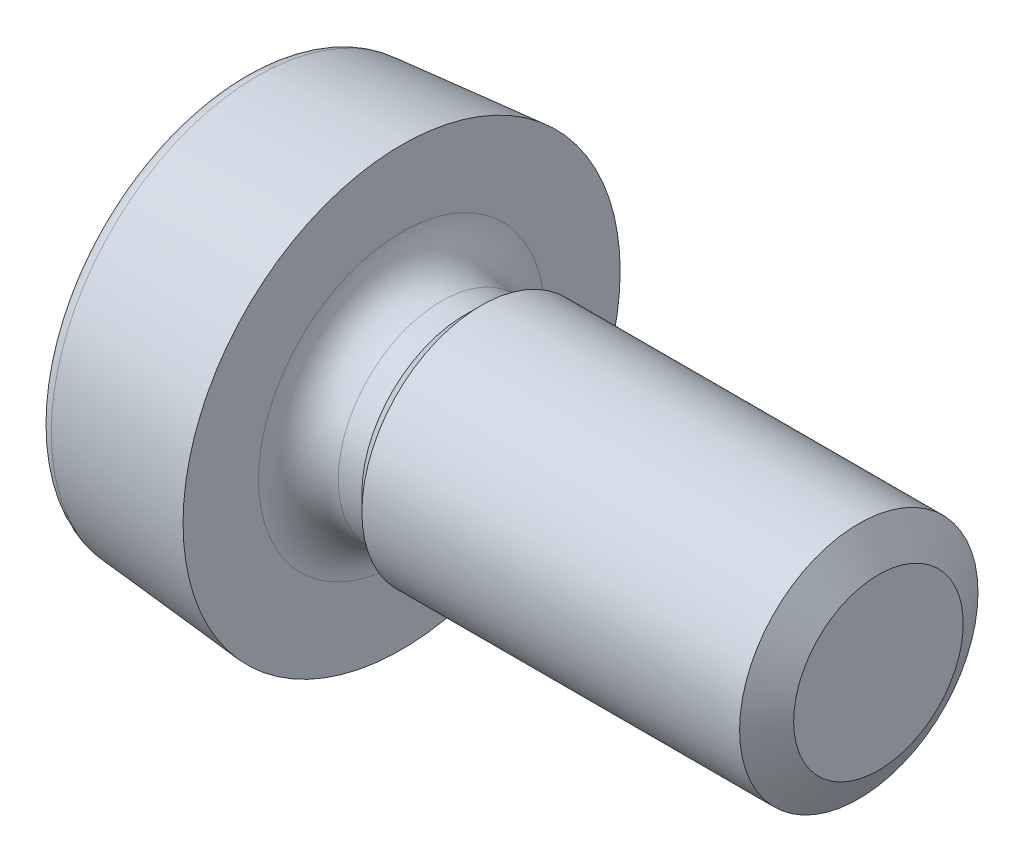
SolidWorks part; units mm, degrees
revolve "基体-旋转" add sketch "草图3" angle 360 about L0
sketch "草图3" plane through (0, 0, 0) normal (0, 0, 1) x (1, 0, 0)
  line L0 (-2.1696, 0) -> (16.014, 0) construction
  line L1 (0, 0) -> (8, 0)
  line L2 (8, 0) -> (8, 1.5)
  line L3 (8, 1.5) -> (3, 1.5)
  line L4 (3, 1.5) -> (2.799, 1.299)
  line L5 (2.799, 1.299) -> (2.501, 1.299)
  line L7 (2, 2.75) -> (0.1826, 2.591)
  line L8 (0, 2.3918) -> (0, 0)
  line L9 (2, 1.8) -> (2, 2.75)
  arc A0 (2, 1.8) -> (2.501, 1.299) centre (2.501, 1.8) ccw
  arc A1 (0.1826, 2.591) -> (0, 2.3918) centre (0.2, 2.3918) ccw
  dimension "D4" = 0.2
  dimension "D1" = 5
  dimension "dk" = 5.5
  dimension "d" = 3
  dimension "D2" = 45
  dimension "da" = 3.6
  dimension "k" = 2
  dimension "D3" = 2.598
  dimension "a" = 1
  dimension "l" = 6
cosmetic thread "装饰螺纹线1" parameters "D2"=2.598
material "AISI 304"
ref_plane "前视" through (0, 0, 0) normal (0, 0, 1) x (1, 0, 0)
ref_plane "上视" through (0, 0, 0) normal (0, 1, 0) x (1, 0, 0)
ref_plane "右视" through (0, 0, 0) normal (1, 0, 0) x (0, 0, -1)
sketch "尺寸草图" plane through (0, 0, 0) normal (0, 0, 1) x (1, 0, 0)
  line L0 (0, 0) -> (6, 0)
  line L1 (0, 0) -> (0, 5.5)
  line L2 (6, 0) -> (6, 3)
  point P5 (0, 3.6)
  point P6 (2, 0)
  point P7 (3, 0)
  point P8 (5.5, 0)
  point P9 (5.14, 0)
  point P10 (2.5, 0)
  point P11 (0, 0.1)
  dimension "dk" = 5.5
  dimension "d" = 3
  dimension "da" = 3.6
  dimension "k" = 2
  dimension "a" = 1
  dimension "l" = 6
  dimension "P" = 0.5
  dimension "h" = 0.86
  dimension "m" = 3.5
  dimension "r" = 0.1
sketch "草图4" plane through (0, 0, 0) normal (0, 0, 1) x (1, 0, 0)
  line L0 (7.7527, 1.5) -> (8.2527, 1.5)
  line L1 (8.2527, 1.5) -> (8, 1.067)
  line L2 (8, 1.067) -> (7.7527, 1.5)
  line L3 (8, 1.5) -> (3, 1.5) construction
  line L4 (8, -1.5) -> (8, 1.5) construction
  line L5 (-0.218, 0) -> (14.7427, 0) construction
  line L6 (-2.1696, 0) -> (16.014, 0) construction
  dimension "D1" = 0.5
  dimension "D2" = 0.433
  dimension "D3" = 60
revolve "切除-旋转1" cut sketch "草图4" angle 360 about L5
pattern_linear "阵列(线性)1" [suppressed] count 10 spacing 0.5 along (1, 0, 0)
sketch "草图5" plane through (0, 0, 0) normal (-1, 0, 0) x (0, 0, 1)
  line L1 (-0.25, 1.75) -> (0.25, 1.75)
  line L2 (-0.25, 1.75) -> (-0.25, -1.75)
  line L3 (-0.25, -1.75) -> (0.25, -1.75)
  line L4 (0.25, 1.75) -> (0.25, -1.75)
  point P4 (-0.25, 0)
  point P5 (0, 1.75)
  dimension "m" = 3.5
  dimension "D1" = 0.5
ref_plane "基准面1" through (0.86, 0, 0) normal (1, 0, 0) x (0, 0, -1)
sketch "草图6" plane through (0.86, 0, 0) normal (1, 0, 0) x (0, 0, -1)
  point P0 (0, 0)
loft "切除-放样1" cut profiles "草图5", "草图6"
pattern_circular "阵列(圆周)1" count 2 every 90 about axis through (0, 0, 0) along (1, 0, 0) of "切除-放样1"
equation "\"l@草图3\" = \"l@尺寸草图\""
equation "\"dk@草图3\" = \"dk@尺寸草图\""
equation "\"da@草图3\" = \"da@尺寸草图\""
equation "\"D4@草图3\" = \"r@尺寸草图\"*2"
equation "\"k@草图3\" = \"k@尺寸草图\""
equation "\"a@草图3\" = \"a@尺寸草图\""
equation "\"D3@草图3\" = \"d@尺寸草图\"*0.866"
equation "\"d@草图3\" = \"d@尺寸草图\""
equation "\"D2@装饰螺纹线1\" = \"d@尺寸草图\"*0.866"
equation "\"D1@草图4\" = \"P@尺寸草图\""
equation "\"D2@草图4\" = \"P@尺寸草图\"*0.866"
equation "\"D3@阵列(线性)1\" = \"P@尺寸草图\""
equation "\"D1@阵列(线性)1\" = (\"l@尺寸草图\"-\"a@尺寸草图\")/\"P@尺寸草图\""
equation "\"D1@基准面1\" = \"h@尺寸草图\""
equation "\"m@草图5\" = \"m@尺寸草图\""
equation "\"D1@草图5\" = \"P@尺寸草图\""
